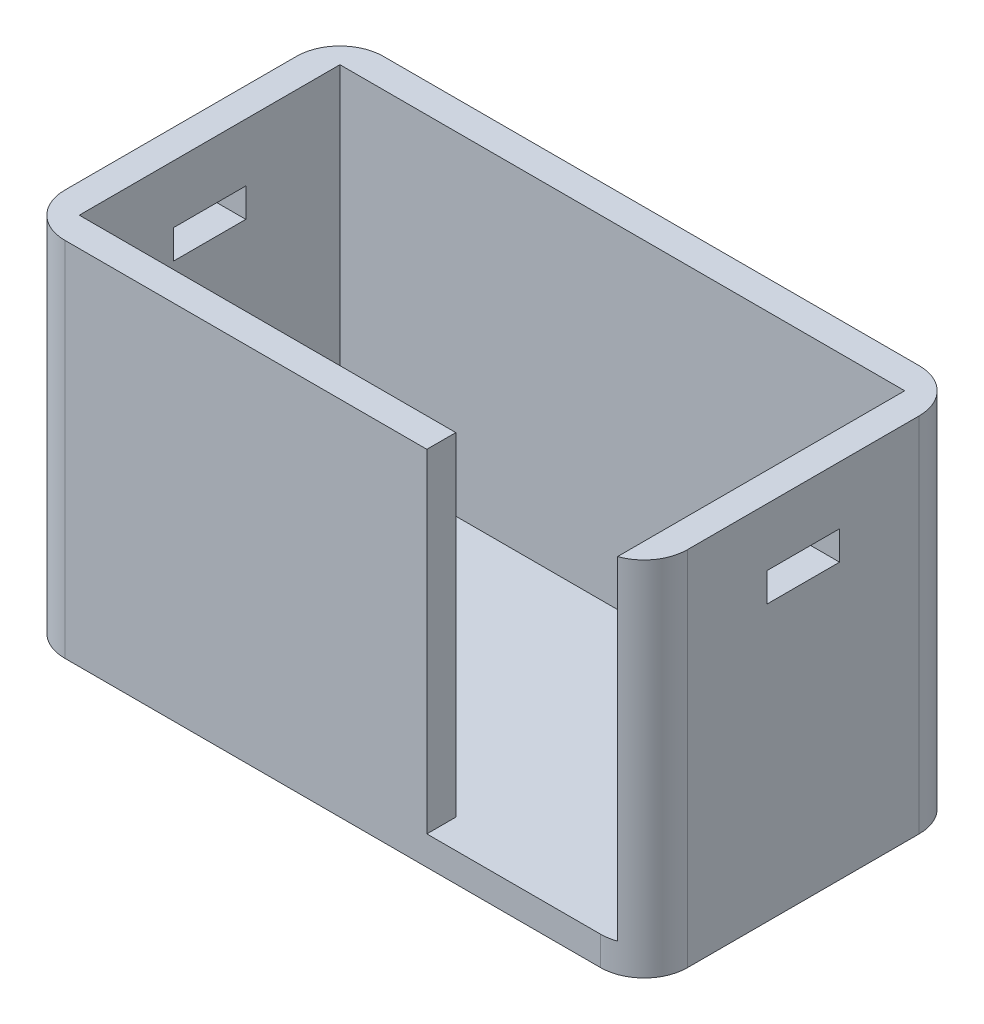
SolidWorks part; units mm, degrees
ref_plane "Front Plane" through (0, 0, 0) normal (0, 0, 1) x (1, 0, 0)
ref_plane "Top Plane" through (0, 0, 0) normal (0, 1, 0) x (1, 0, 0)
ref_plane "Right Plane" through (0, 0, 0) normal (1, 0, 0) x (0, 0, -1)
sketch "Sketch1" plane through (0, 0, 0) normal (0, 0, 1) x (1, 0, 0)
  line L0 (-2, 2) -> (-2, -23)
  line L1 (0, 0) -> (39, 0)
  line L2 (0, 0) -> (0, -21)
  line L3 (0, -21) -> (39, -21)
  line L4 (39, 0) -> (39, -21)
  line L5 (-2, -23) -> (41, -23)
  line L6 (41, 2) -> (41, -23)
  line L7 (-2, 2) -> (41, 2)
  dimension "D1" = 39
  dimension "D2" = 21
  dimension "D3" = 2
extrude "Boss-Extrude1" add sketch "Sketch1" along normal blind 18
sketch "Sketch2" plane through (0, 0, 0) normal (0, 0, -1) x (-1, 0, 0)
  line L1 (-41, 2) -> (2, 2)
  line L2 (-41, 2) -> (-41, -23)
  line L3 (-41, -23) -> (2, -23)
  line L4 (2, 2) -> (2, -23)
extrude "Boss-Extrude2" add sketch "Sketch2" along normal blind 2
sketch "Sketch3" plane through (0, 2, 0) normal (0, 1, 0) x (1, 0, 0)
  line L1 (-2, 2) -> (41, 2)
  line L2 (-2, 2) -> (-2, -18)
  line L3 (-2, -18) -> (41, -18)
  line L4 (41, 2) -> (41, -18)
extrude "Cut-Extrude1" cut sketch "Sketch3" against normal blind 2
sketch "Sketch5" plane through (0, 0, 18) normal (0, 0, 1) x (1, 0, 0)
  line L0 (-2, -23) -> (41, -23) construction
  line L1 (-2, 0) -> (26, 0)
  line L2 (-2, 0) -> (-2, -23)
  line L3 (-2, -23) -> (26, -23)
  line L4 (26, 0) -> (26, -23)
  line L5 (41, -23) -> (41, 0) construction
  dimension "D1" = 15
extrude "Boss-Extrude3" add sketch "Sketch5" along normal blind 2
sketch "Sketch7" plane through (39, 0, 0) normal (-1, 0, 0) x (0, 0, 1)
  line L0 (18, 0) -> (0, 0) construction
  line L1 (6.5, -2) -> (11.5, -2)
  line L2 (6.5, -2) -> (6.5, -4)
  line L3 (6.5, -4) -> (11.5, -4)
  line L4 (11.5, -2) -> (11.5, -4)
  line L5 (0, -21) -> (0, 0) construction
  dimension "D1" = 2
  dimension "D2" = 2
  dimension "D3" = 5
  dimension "D4" = 6.5
extrude "Cut-Extrude3" cut sketch "Sketch7" against normal mid plane 115
sketch "Sketch9" plane through (0, 0, 18) normal (0, 0, 1) x (1, 0, 0)
  line L0 (26, -21) -> (39, -21)
  line L1 (39, -21) -> (39, 0)
  line L2 (39, 0) -> (41, 0)
  line L3 (41, 0) -> (41, -23)
  line L4 (41, -23) -> (26, -23)
  line L5 (26, -23) -> (26, -21)
extrude "Boss-Extrude4" add sketch "Sketch9" along normal blind 2
sketch "Sketch14" plane through (0, 0, 0) normal (0, 1, 0) x (1, 0, 0)
  line L0 (26, -18) -> (26, -20)
  line L1 (26, -20) -> (-2, -20)
  line L2 (-2, -20) -> (-2, 2)
  line L3 (-2, 2) -> (41, 2)
  line L4 (41, 2) -> (41, -20)
  line L5 (41, -20) -> (39, -20)
  line L6 (39, -20) -> (39, 0)
  line L7 (39, 0) -> (0, 0)
  line L8 (0, 0) -> (0, -18)
  line L9 (0, -18) -> (26, -18)
extrude "Boss-Extrude5" add sketch "Sketch14" along normal blind 2
sketch "Sketch18" plane through (0, -23, 0) normal (0, -1, 0) x (1, 0, 0)
  line L0 (41, -2) -> (-2, -2) construction
  line L3 (8.25, 7) -> (8.25, 8.6625)
  line L4 (-2, 20) -> (-2, -2) construction
  line L8 (30.75, 7) -> (30.75, 11.5452)
  circle A0 centre (9.5, 7) radius 1.25
  circle A1 centre (29.5, 7) radius 1.25
  dimension "D1" = 2.5
  dimension "D2" = 2.5
  dimension "D4" = 9
  dimension "D5" = 10.25
  dimension "D3" = 20
extrude "Cut-Extrude4" cut sketch "Sketch18" against normal blind 2 contours A1 | A0
fillet "Fillet4" radius 3 3 edges at (-2, -10.5, 20) (-2, -10.5, -2) (41, -10.5, -2)
fillet "Fillet5" radius 3 1 edges at (41, -10.5, 20)
